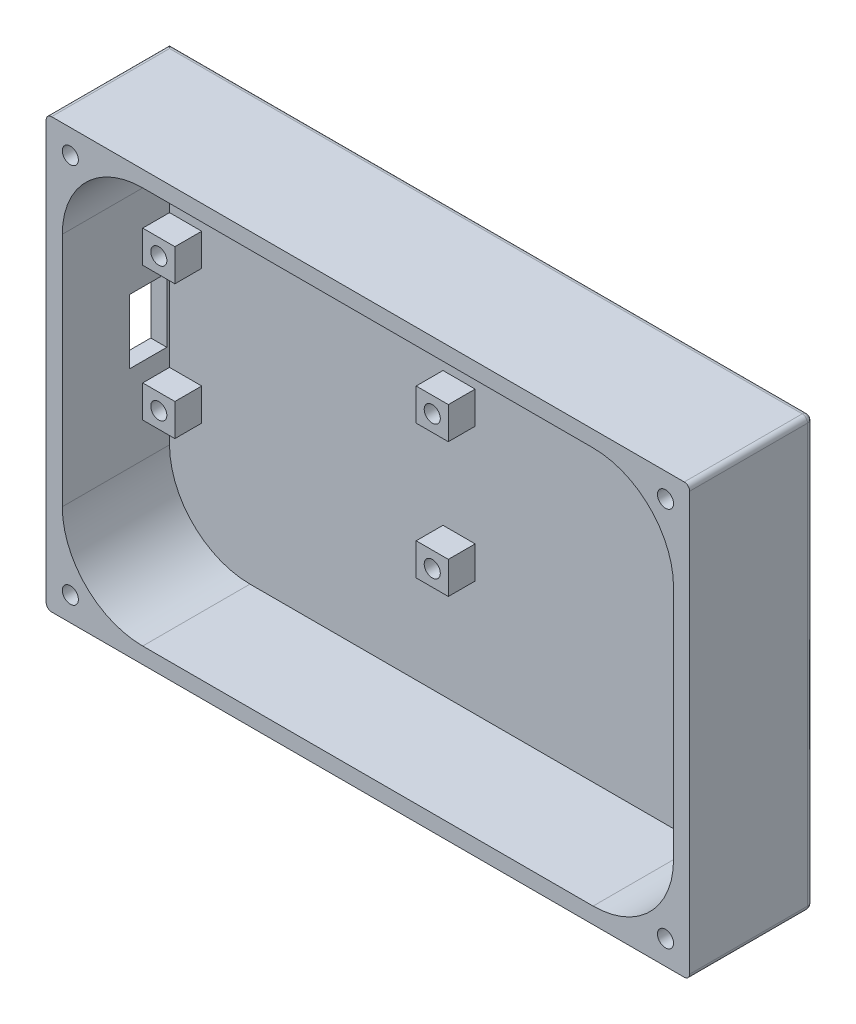
SolidWorks part; units mm, degrees
ref_plane "Plan de face" through (0, 0, 0) normal (0, 0, 1) x (1, 0, 0)
ref_plane "Plan de dessus" through (0, 0, 0) normal (0, 1, 0) x (1, 0, 0)
ref_plane "Plan de droite" through (0, 0, 0) normal (1, 0, 0) x (0, 0, -1)
sketch "Esquisse1" plane through (0, 0, 0) normal (0, 0, 1) x (1, 0, 0)
  line L1 (0, 0) -> (120, 0)
  line L2 (0, 0) -> (0, 80)
  line L3 (0, 80) -> (120, 80)
  line L4 (120, 0) -> (120, 80)
  dimension "D1" = 120
  dimension "D2" = 80
extrude "Boss.-Extru.1" add sketch "Esquisse1" along normal blind 3
sketch "Esquisse4" plane through (0, 0, 3) normal (0, 0, 1) x (1, 0, 0)
  line L1 (0, 80) -> (120, 80)
  line L2 (0, 80) -> (0, 0)
  line L3 (0, 0) -> (120, 0)
  line L4 (120, 80) -> (120, 0)
  line L5 (3, 77) -> (117, 77)
  line L6 (3, 77) -> (3, 3)
  line L7 (3, 3) -> (117, 3)
  line L8 (117, 77) -> (117, 3)
  dimension "D1" = 3
  dimension "D2" = 3
  dimension "D3" = 3
  dimension "D4" = 3
extrude "Boss.-Extru.3" add sketch "Esquisse4" along normal blind 20
fillet "Congé1" radius 15 4 edges at (3, 3, 13) (117, 3, 13) (117, 77, 13) (3, 77, 13)
sketch "Esquisse5" plane through (0, 0, 23) normal (0, 0, 1) x (1, 0, 0)
  line L0 (120, 80) -> (0, 80) construction
  line L1 (0, 80) -> (0, 0) construction
  line L2 (120, 0) -> (120, 80) construction
  line L3 (0, 0) -> (120, 0) construction
  circle A0 centre (4.5, 75.5) radius 1.5
  circle A1 centre (115.5, 75.5) radius 1.5
  circle A2 centre (115.5, 4.5) radius 1.5
  circle A3 centre (4.5, 4.5) radius 1.5
  dimension "D1" = 3
  dimension "D2" = 4.5
  dimension "D3" = 4.5
  dimension "D4" = 4.5
  dimension "D5" = 4.5
  dimension "D6" = 4.5
  dimension "D7" = 4.5
  dimension "D8" = 4.5
  dimension "D9" = 4.5
extrude "Enlèv. mat.-Extru.1" cut sketch "Esquisse5" against normal through all
sketch "Esquisse7" plane through (0, 0, 0) normal (0, 0, -1) x (-1, 0, 0)
  circle A0 centre (-115.5, 75.5) radius 3
  circle A1 centre (-4.5, 75.5) radius 3
  circle A2 centre (-4.5, 4.5) radius 3
  circle A3 centre (-115.5, 4.5) radius 3
  dimension "D1" = 6
extrude "Enlèv. mat.-Extru.3" cut sketch "Esquisse7" against normal blind 6
sketch "Esquisse8" plane through (0, 0, 3) normal (0, 0, 1) x (1, 0, 0)
  line L0 (3, 49.5) -> (3, 30.5) construction
  line L1 (3, 55.5) -> (9, 55.5)
  line L2 (3, 55.5) -> (3, 49.5)
  line L3 (3, 49.5) -> (9, 49.5)
  line L4 (9, 55.5) -> (9, 49.5)
  line L5 (54, 55.5) -> (60, 55.5)
  line L6 (54, 55.5) -> (54, 49.5)
  line L7 (54, 49.5) -> (60, 49.5)
  line L8 (60, 55.5) -> (60, 49.5)
  line L9 (54, 30.5) -> (60, 30.5)
  line L10 (54, 30.5) -> (54, 24.5)
  line L11 (54, 24.5) -> (60, 24.5)
  line L12 (60, 30.5) -> (60, 24.5)
  line L13 (3, 30.5) -> (9, 30.5)
  line L14 (3, 30.5) -> (3, 24.5)
  line L15 (3, 24.5) -> (9, 24.5)
  line L16 (9, 30.5) -> (9, 24.5)
  line L17 (3, 62) -> (3, 18) construction
  circle A0 centre (6, 52.5) radius 1.5
  circle A1 centre (57, 52.5) radius 1.5
  circle A2 centre (57, 27.5) radius 1.5
  circle A3 centre (6, 27.5) radius 1.5
  point P16 (3, 27.5)
  point P17 (3, 52.5)
  point P18 (6, 55.5)
  point P19 (57, 55.5)
  point P22 (3, 40)
  point P23 (3, 40)
  dimension "D4" = 3
  dimension "D1" = 6
  dimension "D2" = 25
  dimension "D3" = 51
extrude "Boss.-Extru.4" add sketch "Esquisse8" along normal blind 5
sketch "Esquisse9" plane through (0, 0, 0) normal (-1, 0, 0) x (0, 0, 1)
  line L0 (0, 80) -> (0, 0) construction
  line L5 (3.5, 46) -> (10.5, 46)
  line L6 (3.5, 46) -> (3.5, 34)
  line L7 (3.5, 34) -> (10.5, 34)
  line L8 (10.5, 46) -> (10.5, 34)
  point P4 (3.5, 40)
  point P7 (0, 40)
  point P8 (7, 46)
  dimension "D1" = 12
  dimension "D2" = 7
  dimension "D3" = 7
extrude "Enlèv. mat.-Extru.4" cut sketch "Esquisse9" against normal up to next
fillet "Congé3" radius 1 7 edges at (60, 80, 0) (0, 80, 11.5) (0, 0, 11.5) (60, 0, 0) (120, 0, 11.5) (120, 40, 0) (120, 80, 11.5)
